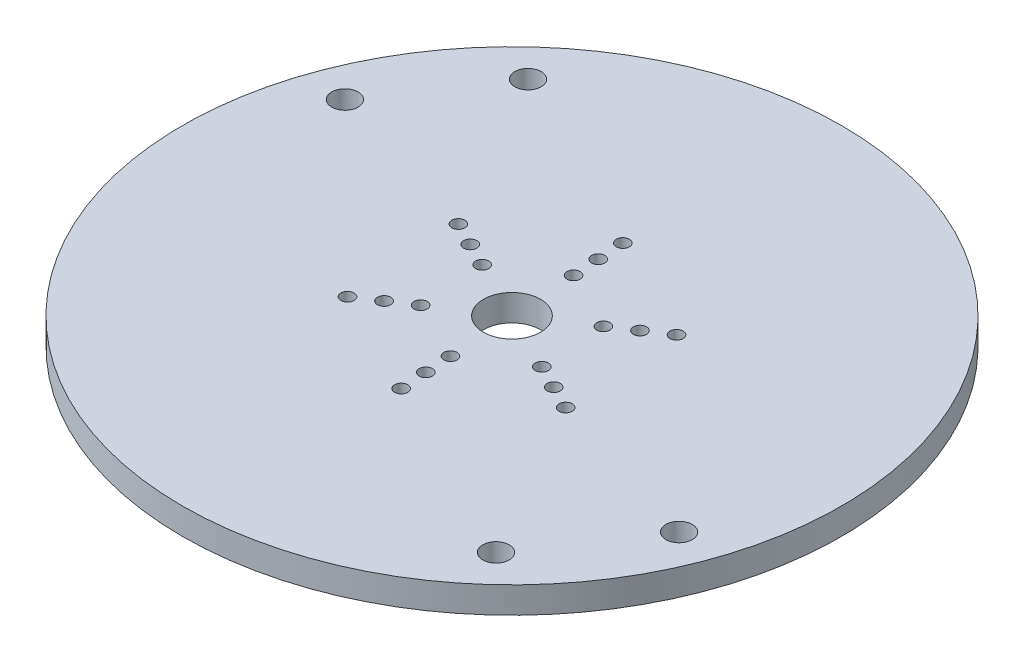
SolidWorks part; units mm, degrees
material "Aluminium 1050"
ref_plane "Front Plane" through (0, 0, 0) normal (0, 0, 1) x (1, 0, 0)
ref_plane "Top Plane" through (0, 0, 0) normal (0, 1, 0) x (1, 0, 0)
ref_plane "Right Plane" through (0, 0, 0) normal (1, 0, 0) x (0, 0, -1)
sketch "Sketch1" plane through (0, 0, 0) normal (0, 1, 0) x (1, 0, 0)
  circle A0 centre (0, 0) radius 37.5
  circle A1 centre (-0.8632, 13.4724) radius 0.75
  circle A2 centre (-0.6713, 10.4785) radius 0.75
  circle A3 centre (-0.4795, 7.4847) radius 0.75
  circle A4 centre (6.2421, 4.1576) radius 0.75
  circle A5 centre (8.739, 5.8207) radius 0.75
  circle A6 centre (11.2358, 7.4837) radius 0.75
  circle A7 centre (-12.099, 5.9887) radius 0.75
  circle A8 centre (-9.4103, 4.6579) radius 0.75
  circle A9 centre (-6.7217, 3.327) radius 0.75
  circle A10 centre (6.7217, -3.327) radius 0.75
  circle A11 centre (9.4103, -4.6579) radius 0.75
  circle A12 centre (12.099, -5.9887) radius 0.75
  circle A13 centre (-11.2358, -7.4837) radius 0.75
  circle A14 centre (-8.739, -5.8207) radius 0.75
  circle A15 centre (-6.2421, -4.1576) radius 0.75
  circle A16 centre (0.4795, -7.4847) radius 0.75
  circle A17 centre (0.6713, -10.4785) radius 0.75
  circle A18 centre (0.8632, -13.4724) radius 0.75
  circle A19 centre (0, 0) radius 3.25
  circle A20 centre (-22.4066, 24.2269) radius 1.5
  circle A21 centre (-30.8159, 11.8059) radius 1.5
  circle A22 centre (30.8159, -11.8059) radius 1.5
  circle A23 centre (22.4066, -24.2269) radius 1.5
  dimension "D1" = 75
  dimension "D2" = 1.5
extrude "Boss-Extrude1" add sketch "Sketch1" along normal blind 3
